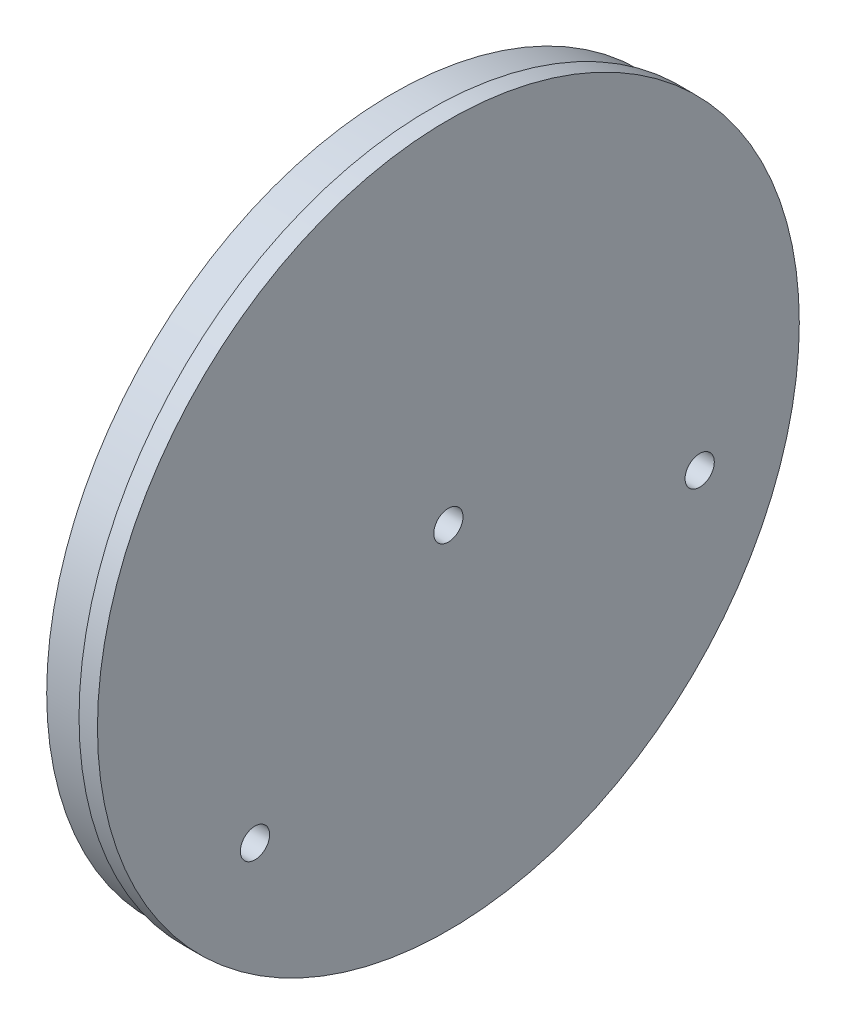
SolidWorks part; units mm, degrees
material "Baltic Birch"
ref_plane "Front Plane" through (0, 0, 0) normal (0, 0, 1) x (1, 0, 0)
ref_plane "Top Plane" through (0, 0, 0) normal (0, 1, 0) x (1, 0, 0)
ref_plane "Right Plane" through (0, 0, 0) normal (1, 0, 0) x (0, 0, -1)
sketch "Sketch1" plane through (0, 0, 0) normal (1, 0, 0) x (0, 0, -1)
  circle A0 centre (0, 0) radius 76.2
  dimension "D1" = 152.4
extrude "Boss-Extrude1" add sketch "Sketch1" along normal blind 12
sketch "Sketch2" plane through (0, 0, 0) normal (-1, 0, 0) x (0, 0, 1)
  circle A0 centre (0, 0) radius 75.2221
  dimension "D1" = 150.4442
extrude "Cut-Extrude1" cut sketch "Sketch2" against normal blind 8 flip side to cut
sketch "Sketch3" plane through (12, 0, 0) normal (1, 0, 0) x (0, 0, -1)
  circle A0 centre (0, 0) radius 3.175
  dimension "D1" = 6.35
extrude "Cut-Extrude2" cut sketch "Sketch3" against normal through all
sketch "Sketch4" plane through (12, 0, 0) normal (1, 0, 0) x (0, 0, -1)
  circle A0 centre (0, 0) radius 57.15 construction
  dimension "D1" = 114.3
sketch "Sketch5" plane through (12, 0, 0) normal (1, 0, 0) x (0, 0, -1)
  circle A0 centre (-41.994, -38.7637) radius 3.175
  circle A1 centre (0, 0) radius 57.15 construction
  dimension "D1" = 6.35
extrude "Cut-Extrude3" cut sketch "Sketch5" against normal through all
pattern_circular "CirPattern1" count 3 over 360 about axis through (12, 0, 0) along (1, 0, 0) skipping 2 of "Cut-Extrude3"
